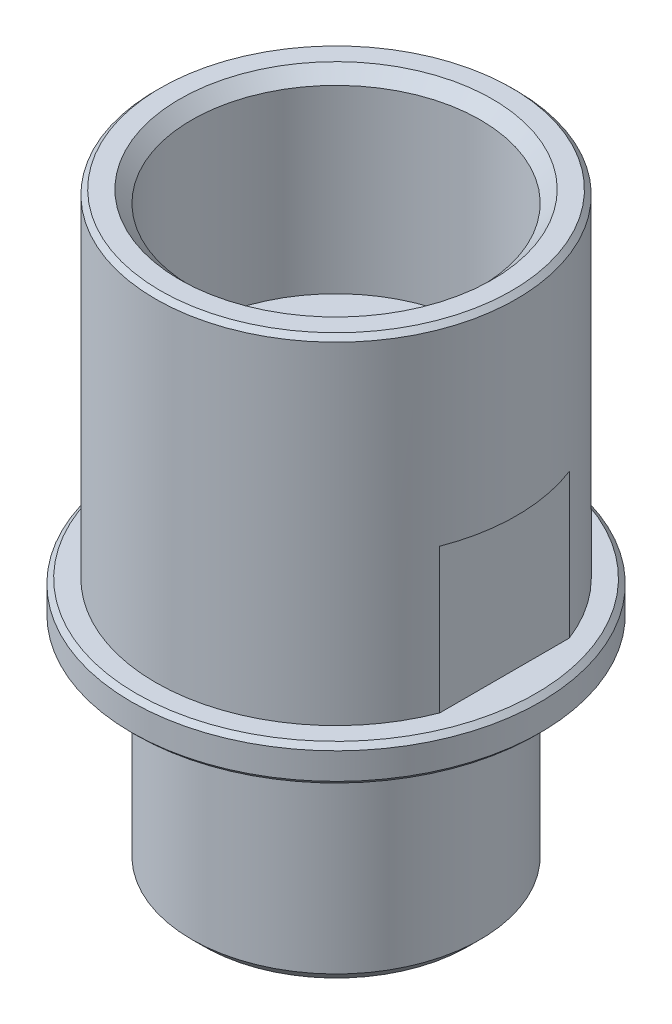
SolidWorks part; units mm, degrees
material "1.4301 (X5CrNi18-10)"
ref_plane "Ebene vorne" through (0, 0, 0) normal (0, 0, 1) x (1, 0, 0)
ref_plane "Ebene oben" through (0, 0, 0) normal (0, 1, 0) x (1, 0, 0)
ref_plane "Ebene rechts" through (0, 0, 0) normal (1, 0, 0) x (0, 0, -1)
sketch "Skizze1" plane through (0, 0, 0) normal (0, 1, 0) x (1, 0, 0)
  circle A0 centre (0, 0) radius 8.5
  dimension "D1" = 17
extrude "GK" add sketch "Skizze1" along normal blind 15.5
sketch "Skizze2" plane through (0, 15.5, 0) normal (0, 1, 0) x (1, 0, 0)
  circle A0 centre (0, 0) radius 7.5
  circle A1 centre (0, 0) radius 8.5
  dimension "D1" = 15
extrude "D15" cut sketch "Skizze2" against normal blind 14
ref_plane "Ebene1" through (7.5, 0, 0) normal (1, 0, 0) x (0, 0, -1)
sketch "Skizze3" plane through (7.5, 0, 0) normal (1, 0, 0) x (0, 0, -1)
  line L0 (0, 0) -> (0, 15.5) construction
  line L1 (7.5, 15.5) -> (-7.5, 15.5) construction
  line L2 (8.5, 1.5) -> (-8.5, 1.5) construction
  line L3 (-7.5, 1.5) -> (7.5, 1.5)
  line L4 (-7.5, 1.5) -> (-7.5, 7.5)
  line L5 (-7.5, 7.5) -> (7.5, 7.5)
  line L6 (7.5, 1.5) -> (7.5, 7.5)
  dimension "D1" = 15
  dimension "D2" = 6
extrude "SW14" cut sketch "Skizze3" against normal blind 0.5
mirror "Spiegeln1" about plane through (0, 0, 0) normal (1, 0, 0) of "SW14"
sketch "Skizze4" plane through (0, 0, 0) normal (0, -1, 0) x (1, 0, 0)
  circle A0 centre (0, 0) radius 6
  dimension "D1" = 12
extrude "Außengewinde" add sketch "Skizze4" along normal blind 9
cosmetic thread "M12x0,75" parameters "D1"=9, "D2"=11.08
sketch "Skizze18" plane through (0, -9, 0) normal (0, -1, 0) x (1, 0, 0)
  circle A0 centre (0, 0) radius 4.65
  dimension "D1" = 9.3
extrude "D9,3mm" cut sketch "Skizze18" against normal through all
sketch "Skizze19" plane through (0, 15.5, 0) normal (0, 1, 0) x (1, 0, 0)
  circle A0 centre (0, 0) radius 6
  dimension "D1" = 12
extrude "Kernloch D12" cut sketch "Skizze19" against normal blind 8
cosmetic thread "M13x1" parameters "D1"=7, "D2"=14
chamfer "Fase 0,2mm" distance 0.2 angle 45 3 edges at (0, 15.5, 7.5) (0, 0, 8.5) (0, 1.5, 8.5)
chamfer "Fase 0,5mm" distance 0.5 2 edges at (0, 15.5, 6) (0, -9, -6)
